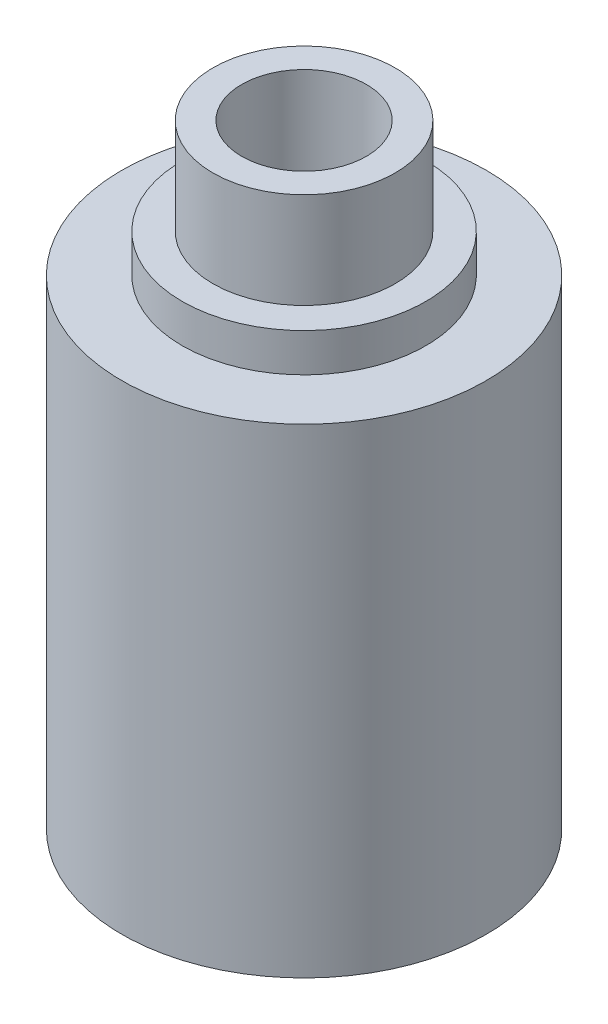
SolidWorks part; units mm, degrees
ref_plane "前视基准面" through (0, 0, 0) normal (0, 0, 1) x (1, 0, 0)
ref_plane "上视基准面" through (0, 0, 0) normal (0, 1, 0) x (1, 0, 0)
ref_plane "右视基准面" through (0, 0, 0) normal (1, 0, 0) x (0, 0, -1)
sketch "草图1" plane through (0, 0, 0) normal (0, 1, 0) x (1, 0, 0)
  circle A0 centre (0, 0) radius 6.35
  dimension "D1" = 12.7
extrude "凸台-拉伸1" add sketch "草图1" along normal blind 2
sketch "草图2" plane through (0, 2, 0) normal (0, 1, 0) x (1, 0, 0)
  circle A0 centre (0, 0) radius 4.75
  dimension "D1" = 9.5
extrude "凸台-拉伸2" add sketch "草图2" along normal blind 5
sketch "草图3" plane through (0, 7, 0) normal (0, 1, 0) x (1, 0, 0)
  circle A0 centre (0, 0) radius 3.25
  dimension "D1" = 6.5
extrude "切除-拉伸1" cut sketch "草图3" against normal through all
sketch "草图4" plane through (0, 0, 0) normal (0, -1, 0) x (1, 0, 0)
  circle A0 centre (0, 0) radius 9.5
  dimension "D1" = 19
extrude "凸台-拉伸3" add sketch "草图4" along normal blind 25
